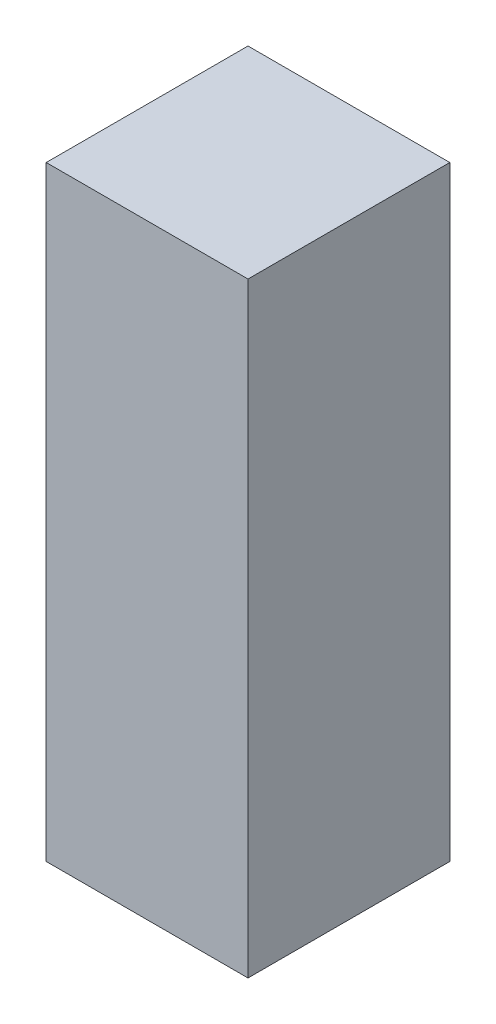
SolidWorks part; units mm, degrees
ref_plane "前视基准面" through (0, 0, 0) normal (0, 0, 1) x (1, 0, 0)
ref_plane "上视基准面" through (0, 0, 0) normal (0, 1, 0) x (1, 0, 0)
ref_plane "右视基准面" through (0, 0, 0) normal (1, 0, 0) x (0, 0, -1)
sketch "草图1" plane through (0, 0, 0) normal (0, 1, 0) x (1, 0, 0)
  line L1 (-500, 500) -> (500, 500)
  line L2 (-500, 500) -> (-500, -500)
  line L3 (-500, -500) -> (500, -500)
  line L4 (500, 500) -> (500, -500)
  line L5 (-500, 500) -> (500, -500) construction
  line L6 (-500, -500) -> (500, 500) construction
  point P0 (0, 0)
extrude "凸台-拉伸1" add sketch "草图1" along normal blind 3000
